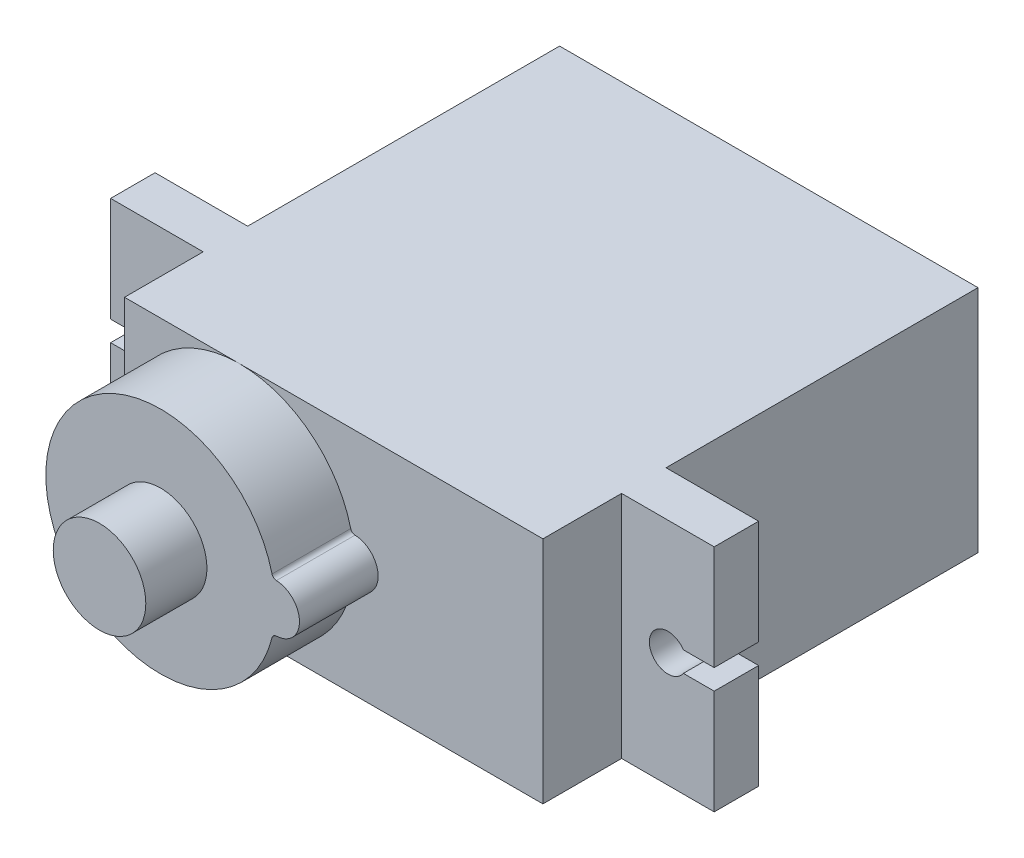
SolidWorks part; units mm, degrees
ref_plane "Front Plane" through (0, 0, 0) normal (0, 0, 1) x (1, 0, 0)
ref_plane "Top Plane" through (0, 0, 0) normal (0, 1, 0) x (1, 0, 0)
ref_plane "Right Plane" through (0, 0, 0) normal (1, 0, 0) x (0, 0, -1)
sketch "Sketch1" plane through (0, 0, 0) normal (0, 0, 1) x (1, 0, 0)
  line L1 (11.3, -6.2) -> (-11.3, -6.2)
  line L2 (11.3, -6.2) -> (11.3, 6.2)
  line L3 (11.3, 6.2) -> (-11.3, 6.2)
  line L4 (-11.3, -6.2) -> (-11.3, 6.2)
  line L5 (11.3, -6.2) -> (-11.3, 6.2) construction
  line L6 (11.3, 6.2) -> (-11.3, -6.2) construction
  point P0 (0, 0)
  dimension "D1" = 22.6
  dimension "D2" = 12.4
extrude "Boss-Extrude1" add sketch "Sketch1" along normal blind 23.5
sketch "Sketch3" plane through (0, -6.2, 0) normal (0, -1, 0) x (1, 0, 0)
  line L0 (11.3, 23.5) -> (11.3, 0) construction
  line L1 (11.3, 16.85) -> (16.3, 16.85)
  line L2 (11.3, 16.85) -> (11.3, 19.25)
  line L3 (11.3, 19.25) -> (16.3, 19.25)
  line L4 (16.3, 16.85) -> (16.3, 19.25)
  line L5 (0, 0) -> (0, 23.5) construction
  line L6 (-11.3, 0) -> (11.3, 0) construction
  line L7 (-11.3, 23.5) -> (11.3, 23.5) construction
  line L8 (-11.3, 19.25) -> (-16.3, 19.25)
  line L9 (-16.3, 16.85) -> (-16.3, 19.25)
  line L10 (-11.3, 16.85) -> (-16.3, 16.85)
  line L11 (-11.3, 16.85) -> (-11.3, 19.25)
  dimension "D1" = 4.25
  dimension "D2" = 2.4
  dimension "D3" = 5
extrude "Boss-Extrude2" add sketch "Sketch3" against normal up to surface (12.4 mm away) up to face at (0, 6.2, 11.75)
sketch "Sketch4" plane through (0, 0, 19.25) normal (0, 0, 1) x (1, 0, 0)
  line L0 (-16.3, 0) -> (16.3, 0) construction
  line L1 (-16.3, 6.2) -> (-16.3, -6.2) construction
  line L2 (16.3, 6.2) -> (16.3, -6.2) construction
  line L3 (0, 6.2) -> (0, -6.2) construction
  line L4 (11.3, 6.2) -> (-11.3, 6.2) construction
  line L5 (-11.3, -6.2) -> (11.3, -6.2) construction
  line L6 (16.3, 0.55) -> (16.3, -0.55)
  line L7 (-16.3, 0.55) -> (-14.6352, 0.55)
  line L8 (-16.3, 0.55) -> (-16.3, -0.55)
  line L9 (-16.3, -0.55) -> (-14.6352, -0.55)
  line L11 (16.3, 0.55) -> (14.6352, 0.55)
  line L12 (16.3, -0.55) -> (14.6352, -0.55)
  arc A0 (-14.6352, -0.55) -> (-14.6352, 0.55) centre (-13.8, 0) ccw
  arc A1 (14.6352, -0.55) -> (14.6352, 0.55) centre (13.8, 0) cw
  dimension "D1" = 2
  dimension "D2" = 2.5
  dimension "D3" = 1.1
extrude "Cut-Extrude1" cut sketch "Sketch4" against normal through all
sketch "Sketch5" plane through (0, 0, 23.5) normal (0, 0, 1) x (1, 0, 0)
  line L0 (-17.4923, 0) -> (17.8092, 0) construction
  line L1 (0, 6.2) -> (0, -6.2) construction
  line L2 (11.3, 6.2) -> (-11.3, 6.2) construction
  line L3 (-11.3, -6.2) -> (11.3, -6.2) construction
  line L4 (-11.3, 6.2) -> (-11.3, -6.2) construction
  arc A0 (0.9186, 1.4888) -> (0.9186, -1.4888) centre (-5.1, 0) ccw
  arc A2 (1.1514, -1.299) -> (1.1514, 1.299) centre (1.1, 0) ccw
  arc A3 (1.1514, -1.299) -> (0.9186, -1.4888) centre (1.1613, -1.5488) ccw
  arc A4 (1.1514, 1.299) -> (0.9186, 1.4888) centre (1.1613, 1.5488) cw
  dimension "D1" = 12.4
  dimension "D2" = 0.25
  dimension "D3" = 1.3
extrude "Boss-Extrude3" add sketch "Sketch5" along normal blind 4.25 contours A0 A3 A2 A4
sketch "Sketch6" plane through (0, 0, 27.75) normal (0, 0, 1) x (1, 0, 0)
  circle A0 centre (-5.1, 0) radius 2.5
  dimension "D1" = 5
extrude "Boss-Extrude4" add sketch "Sketch6" along normal blind 3.3
